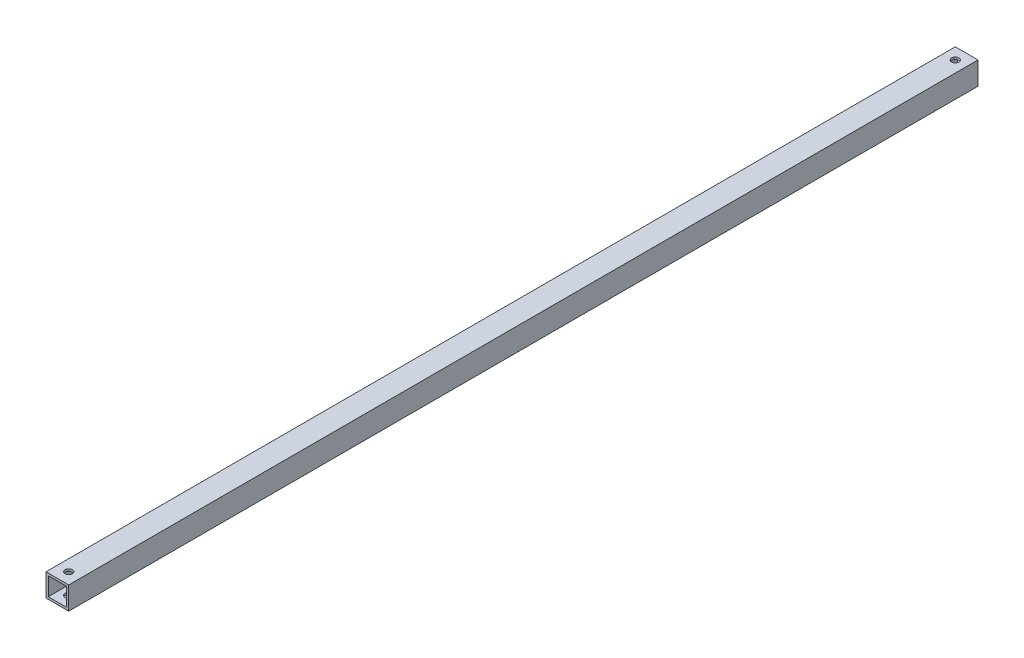
SolidWorks part; units mm, degrees
ref_plane "正面" through (0, 0, 0) normal (0, 0, 1) x (1, 0, 0)
ref_plane "平面" through (0, 0, 0) normal (0, 1, 0) x (1, 0, 0)
ref_plane "右側面" through (0, 0, 0) normal (1, 0, 0) x (0, 0, -1)
sketch "ｽｹｯﾁ1" plane through (0, 0, 0) normal (0, 0, 1) x (1, 0, 0)
  line L0 (-4, 4) -> (-4, -4)
  line L1 (-5, 5) -> (5, 5)
  line L2 (-5, 5) -> (-5, -5)
  line L3 (-5, -5) -> (5, -5)
  line L4 (5, 5) -> (5, -5)
  line L5 (-5, 5) -> (5, -5) construction
  line L6 (-5, -5) -> (5, 5) construction
  line L7 (-4, -4) -> (4, -4)
  line L8 (4, 4) -> (4, -4)
  line L9 (-4, 4) -> (4, 4)
  point P0 (0, 0)
  dimension "D1" = 10
  dimension "D2" = 10
  dimension "D3" = 1
extrude "ﾎﾞｽ - 押し出し1" add sketch "ｽｹｯﾁ1" along normal blind 399.7114
sketch "ｽｹｯﾁ2" plane through (0, 5, 0) normal (0, 1, 0) x (1, 0, 0)
  line L0 (5, -399.7114) -> (-5, -399.7114) construction
  line L1 (5, 0) -> (-5, 0) construction
  circle A0 centre (0, -5) radius 1.6
  circle A1 centre (0, -394.7114) radius 1.6
  dimension "D1" = 5
  dimension "D2" = 3.2
  dimension "D3" = 5
  dimension "D4" = 3.2
extrude "ｶｯﾄ - 押し出し1" cut sketch "ｽｹｯﾁ2" against normal blind 408.3717
